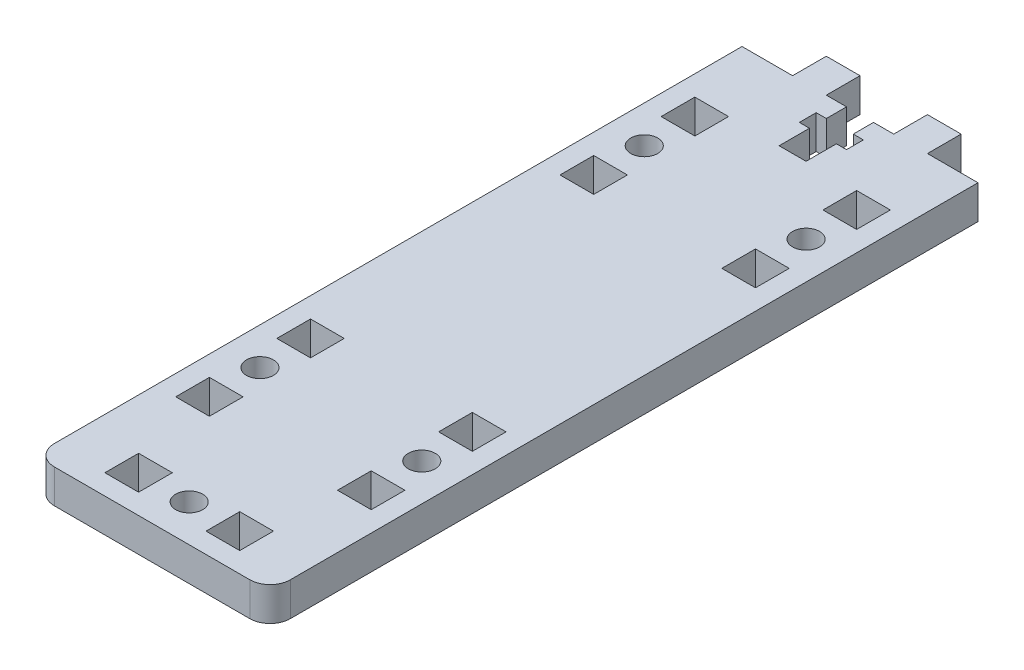
SolidWorks part; units mm, degrees
ref_plane "Front Plane" through (0, 0, 0) normal (0, 0, 1) x (1, 0, 0)
ref_plane "Top Plane" through (0, 0, 0) normal (0, 1, 0) x (1, 0, 0)
ref_plane "Right Plane" through (0, 0, 0) normal (1, 0, 0) x (0, 0, -1)
sketch "Sketch1" plane through (0, 0, 0) normal (0, 1, 0) x (1, 0, 0)
  line L0 (-26.0562, 5.5016) -> (-21.0562, 5.5016)
  line L1 (-29.0562, 30.5016) -> (-21.5562, 30.5016)
  line L2 (-29.0562, 30.5016) -> (-29.0562, -74.4984)
  line L3 (-29.0562, -74.4984) -> (5.9438, -74.4984)
  line L4 (5.9438, 30.5016) -> (5.9438, -74.4984)
  line L5 (-26.0562, 20.5016) -> (-21.0562, 20.5016)
  line L6 (-26.0562, 20.5016) -> (-26.0562, 15.5016)
  line L7 (-26.0562, 15.5016) -> (-21.0562, 15.5016)
  line L8 (-21.0562, 20.5016) -> (-21.0562, 15.5016)
  line L9 (-26.0562, 5.5016) -> (-26.0562, 0.5016)
  line L10 (-26.0562, 0.5016) -> (-21.0562, 0.5016)
  line L11 (-21.0562, 5.5016) -> (-21.0562, 0.5016)
  line L12 (-11.5562, 30.5016) -> (-11.5562, -74.4984) construction
  line L13 (-2.0562, 5.5016) -> (-2.0562, 0.5016)
  line L14 (2.9438, 0.5016) -> (-2.0562, 0.5016)
  line L15 (2.9438, 5.5016) -> (2.9438, 0.5016)
  line L16 (2.9438, 5.5016) -> (-2.0562, 5.5016)
  line L17 (-2.0562, 20.5016) -> (-2.0562, 15.5016)
  line L18 (2.9438, 15.5016) -> (-2.0562, 15.5016)
  line L19 (2.9438, 20.5016) -> (2.9438, 15.5016)
  line L20 (2.9438, 20.5016) -> (-2.0562, 20.5016)
  line L21 (-29.0562, -17.9984) -> (5.9438, -17.9984) construction
  line L22 (2.9438, -41.4984) -> (2.9438, -36.4984)
  line L23 (2.9438, -36.4984) -> (-2.0562, -36.4984)
  line L24 (-2.0562, -41.4984) -> (-2.0562, -36.4984)
  line L25 (2.9438, -41.4984) -> (-2.0562, -41.4984)
  line L26 (2.9438, -51.4984) -> (-2.0562, -51.4984)
  line L27 (2.9438, -56.4984) -> (2.9438, -51.4984)
  line L28 (2.9438, -56.4984) -> (-2.0562, -56.4984)
  line L29 (-2.0562, -56.4984) -> (-2.0562, -51.4984)
  line L30 (-21.0562, -56.4984) -> (-21.0562, -51.4984)
  line L31 (-26.0562, -56.4984) -> (-21.0562, -56.4984)
  line L32 (-26.0562, -56.4984) -> (-26.0562, -51.4984)
  line L33 (-26.0562, -51.4984) -> (-21.0562, -51.4984)
  line L34 (-21.0562, -41.4984) -> (-21.0562, -36.4984)
  line L35 (-26.0562, -36.4984) -> (-21.0562, -36.4984)
  line L36 (-26.0562, -41.4984) -> (-26.0562, -36.4984)
  line L37 (-26.0562, -41.4984) -> (-21.0562, -41.4984)
  line L38 (-21.5562, -66.4984) -> (-21.5562, -71.4984)
  line L39 (-6.5562, -66.4984) -> (-1.5562, -66.4984)
  line L40 (-6.5562, -66.4984) -> (-6.5562, -71.4984)
  line L41 (-6.5562, -71.4984) -> (-1.5562, -71.4984)
  line L42 (-1.5562, -66.4984) -> (-1.5562, -71.4984)
  line L43 (-16.5562, -71.4984) -> (-21.5562, -71.4984)
  line L44 (-16.5562, -66.4984) -> (-16.5562, -71.4984)
  line L45 (-16.5562, -66.4984) -> (-21.5562, -66.4984)
  line L46 (-16.5562, 30.5016) -> (-13.5562, 30.5016)
  line L48 (-21.5562, 30.5016) -> (-21.5562, 35.5016)
  line L49 (-21.5562, 35.5016) -> (-16.5562, 35.5016)
  line L50 (-16.5562, 30.5016) -> (-16.5562, 35.5016)
  line L51 (-1.5562, 30.5016) -> (-1.5562, 35.5016)
  line L52 (-1.5562, 35.5016) -> (-6.5562, 35.5016)
  line L53 (-6.5562, 30.5016) -> (-6.5562, 35.5016)
  line L54 (-1.5562, 30.5016) -> (5.9438, 30.5016)
  line L55 (-9.5562, 25.0016) -> (-8.0562, 25.0016)
  line L57 (-13.5562, 30.5016) -> (-13.5562, 27.5016)
  line L58 (-13.5562, 20.5016) -> (-9.5562, 20.5016)
  line L59 (-9.5562, 30.5016) -> (-9.5562, 27.5016)
  line L60 (-13.5562, 27.5016) -> (-15.0562, 27.5016)
  line L62 (-13.5562, 25.0016) -> (-15.0562, 25.0016)
  line L63 (-15.0562, 27.5016) -> (-15.0562, 25.0016)
  line L64 (-8.0562, 27.5016) -> (-8.0562, 25.0016)
  line L65 (-9.5562, 27.5016) -> (-8.0562, 27.5016)
  line L66 (-9.5562, 30.5016) -> (-6.5562, 30.5016)
  line L67 (-13.5562, 25.0016) -> (-13.5562, 20.5016)
  line L68 (-9.5562, 25.0016) -> (-9.5562, 20.5016)
  circle A0 centre (0.4438, 10.5016) radius 2
  circle A1 centre (-23.5562, 10.5016) radius 2
  circle A2 centre (0.4438, -46.4984) radius 2
  circle A3 centre (-23.5562, -46.4984) radius 2
  circle A4 centre (-11.5562, -68.9984) radius 2
  point P24 (-23.5562, 0.5016)
  dimension "D10" = 4
  dimension "D12" = 4
  dimension "D1" = 35
  dimension "D2" = 105
  dimension "D3" = 5
  dimension "D4" = 3
  dimension "D5" = 10
  dimension "D6" = 10
  dimension "D7" = 18.5
  dimension "D8" = 5
  dimension "D9" = 3
  dimension "D11" = 5
  dimension "D13" = 3
  dimension "D14" = 10
  dimension "D15" = 2.5
  dimension "D16" = 3
  dimension "D17" = 1.5
extrude "Boss-Extrude7" add sketch "Sketch1" along normal blind 5
fillet "Fillet2" radius 3 2 edges at (-29.0562, 2.5, 74.4984) (5.9438, 2.5, 74.4984)
